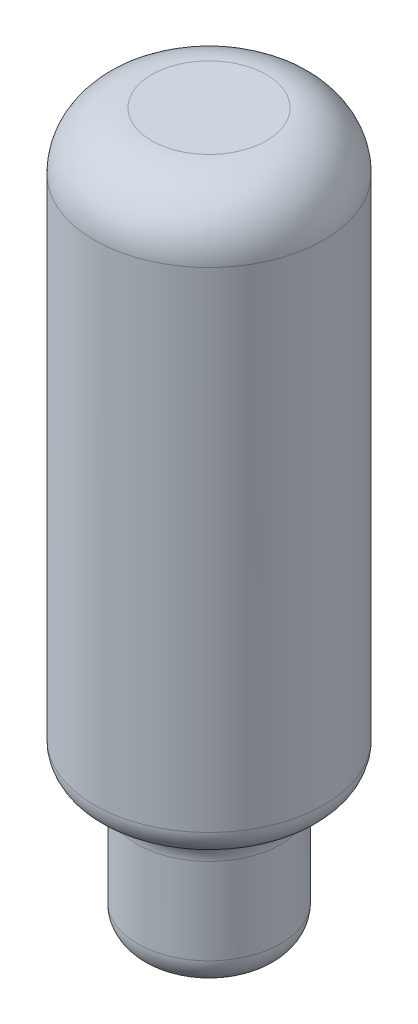
SolidWorks part; units mm, degrees
ref_plane "Front Plane" through (0, 0, 0) normal (0, 0, 1) x (1, 0, 0)
ref_plane "Top Plane" through (0, 0, 0) normal (0, 1, 0) x (1, 0, 0)
ref_plane "Right Plane" through (0, 0, 0) normal (1, 0, 0) x (0, 0, -1)
sketch "Sketch1" plane through (0, 0, 0) normal (0, 1, 0) x (1, 0, 0)
  circle A0 centre (0, 0) radius 4
extrude "Boss-Extrude1" add sketch "Sketch1" along normal blind 20
sketch "Sketch2" plane through (0, 0, 0) normal (0, -1, 0) x (1, 0, 0)
  circle A0 centre (0, 0) radius 2.5
extrude "Boss-Extrude2" add sketch "Sketch2" along normal blind 5
fillet "Fillet1" radius 1 1 edges at (0, 0, -2.5)
fillet "Fillet2" radius 2 1 edges at (0, 20, 4)
fillet "Fillet3" radius 1 1 edges at (0, 0, 4)
fillet "Fillet4" radius 1 1 edges at (0, -5, -2.5)
